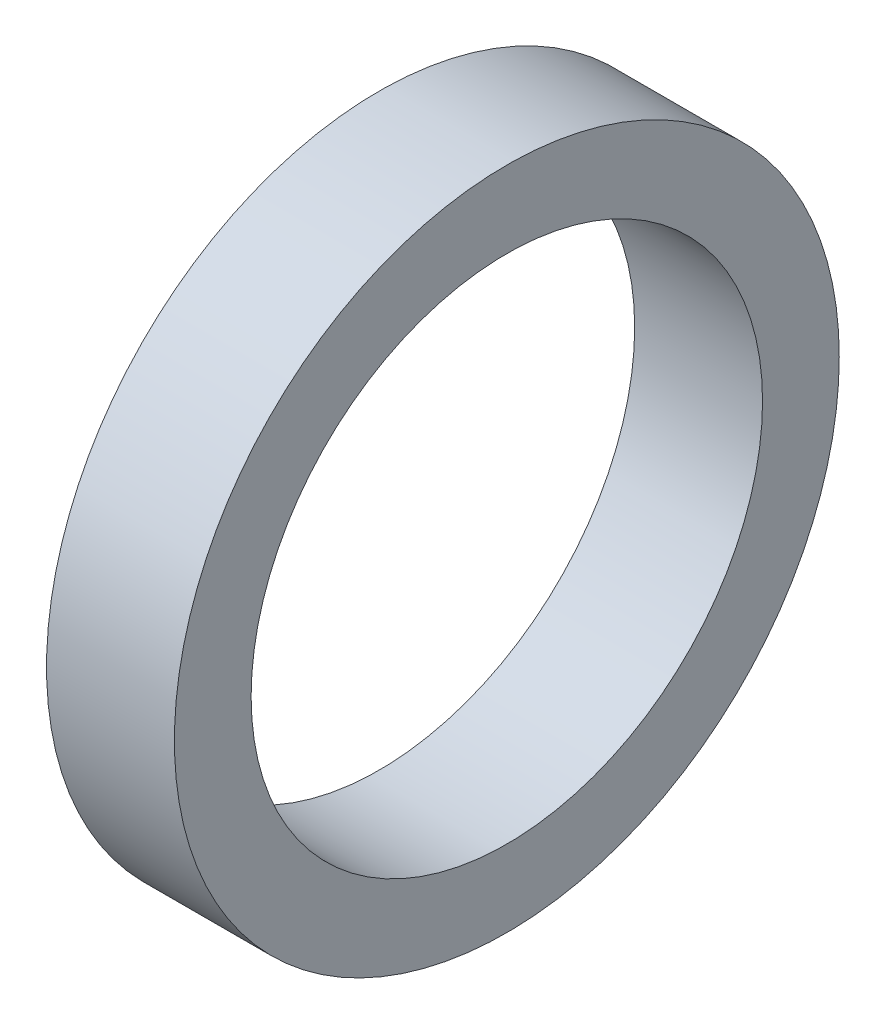
SolidWorks part; units mm, degrees
ref_plane "前视基准面" through (0, 0, 0) normal (0, 0, 1) x (1, 0, 0)
ref_plane "上视基准面" through (0, 0, 0) normal (0, 1, 0) x (1, 0, 0)
ref_plane "右视基准面" through (0, 0, 0) normal (1, 0, 0) x (0, 0, -1)
other "Configuration Table"
sketch "草图1" plane through (0, 0, 0) normal (0, 0, 1) x (1, 0, 0)
  line L0 (0, 0) -> (-5.1169, 0) construction
  line L1 (0, 13) -> (0, 10)
  line L2 (0, 10) -> (5, 10)
  line L3 (5, 10) -> (5, 13)
  line L4 (5, 13) -> (0, 13)
  dimension "D1" = 20
  dimension "D2" = 26
  dimension "D3" = 5
revolve "旋转1" add sketch "草图1" angle 360 about L0
